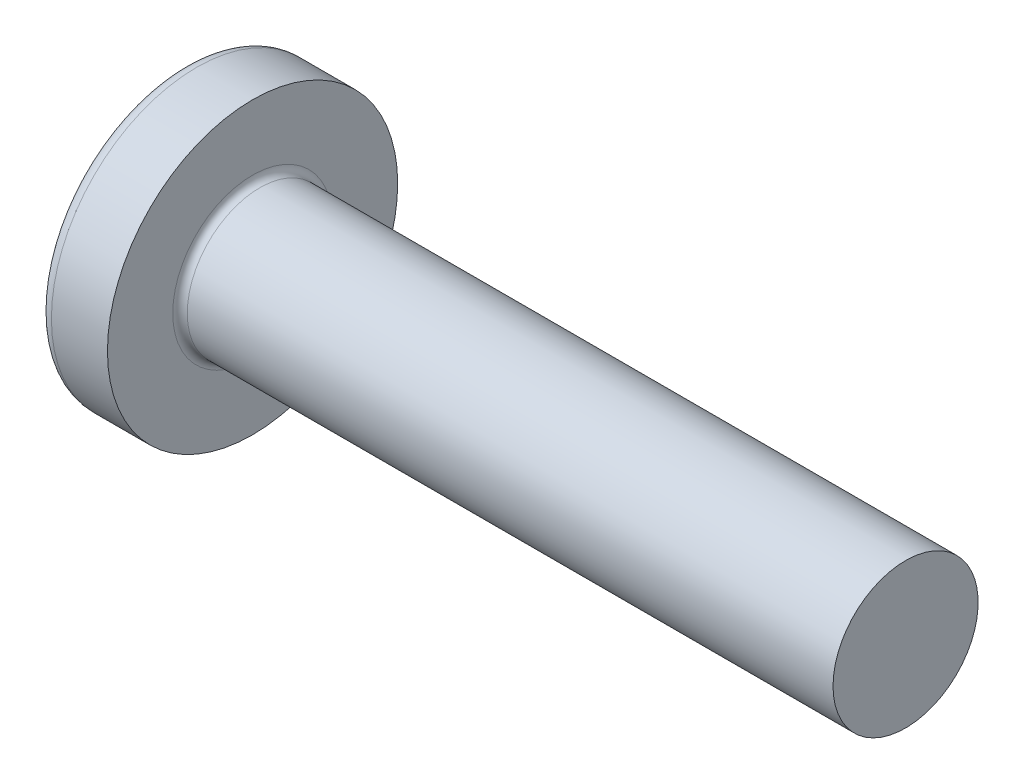
SolidWorks part; units mm, degrees
material "普通碳钢"
ref_plane "Plane1" through (0, 0, 0) normal (0, 0, 1) x (1, 0, 0)
ref_plane "Plane2" through (0, 0, 0) normal (0, 1, 0) x (1, 0, 0)
ref_plane "Plane3" through (0, 0, 0) normal (1, 0, 0) x (0, 0, -1)
sketch "BodySke" plane through (0, 0, 0) normal (0, 0, 1) x (1, 0, 0)
  line L0 (3.1, 2) -> (3.1, 4)
  line L1 (3.45, 6.35) -> (3.45, -3.175) construction
  line L2 (-25.4, 0) -> (127, 0) construction
  line L3 (21.1, 0) -> (0, 0)
  line L4 (3.1, 2) -> (21.1, 2)
  line L5 (21.1, 2) -> (21.1, 0)
  line L6 (1.5553, 4) -> (3.1, 4)
  line L8 (15.1, 6.35) -> (15.1, -3.175) construction
  arc A0 (1.2654, 3.8534) -> (0, 0) centre (6.5, 0) ccw
  arc A2 (1.2654, 3.8534) -> (1.5553, 4) centre (1.5553, 3.64) cw
  dimension "Head_fillet_rad" = 0.36
  dimension "Head_crown_rad" = 6.5
  dimension "Head_ht" = 3.1
  dimension "Diameter" = 4
  dimension "Length" = 18
  dimension "Head_dia" = 8
  dimension "Advance" = 0.7
  dimension "Thread_nom" = 6
revolve "Base-Revolve" add sketch "BodySke"
cosmetic thread "ThreadCosmetic" [suppressed]
fillet "Fillet1" radius 0.2 1 edges at (3.1, 0, 2)
sketch "Sketch3" plane through (0, 0, 0) normal (1, 0, 0) x (0, 0, -1)
  line L0 (0.515, -2.15) -> (-0.515, -2.15)
  line L1 (0.515, -2.15) -> (0.515, 2.15)
  line L2 (-0.515, 2.15) -> (0.515, 2.15)
  line L3 (-0.515, 2.15) -> (-0.515, -2.15)
  dimension "D1" = 2.15
  dimension "Cross_dia" = 4.3
  dimension "D2" = 0.515
  dimension "Cross_width" = 1.03
ref_plane "Plane4" through (2.34, 0, 0) normal (1, 0, 0) x (0, 0, -1)
sketch "Sketch4" plane through (2.34, 0, 0) normal (1, 0, 0) x (0, 0, -1)
  line L0 (0.515, -0.9833) -> (-0.515, -0.9833)
  line L1 (0.515, -0.9833) -> (0.515, 0.9833)
  line L2 (-0.515, 0.9833) -> (0.515, 0.9833)
  line L3 (-0.515, 0.9833) -> (-0.515, -0.9833)
  dimension "D1" = 1.03
  dimension "D2" = 1.9666
  dimension "D3" = 0.515
  dimension "D4" = 0.9833
loft "Recess" cut profiles "Sketch3", "Sketch4"
pattern_circular "RecPat" count 2 every 90 about axis through (0, 0, 0) along (1, 0, 0) of "Recess"
sketch "RecCorSke" plane through (0, 0, 0) normal (0, 0, 1) x (1, 0, 0)
  line L0 (-3.175, 0) -> (15.875, 0) construction
  line L1 (-25.4, 0) -> (127, 0) construction
  line L2 (0, 0) -> (0, 1.0146)
  line L3 (0, 1.0146) -> (2.34, 0.851)
  line L4 (2.34, 0.851) -> (2.6165, 0)
  line L5 (2.6165, 0) -> (0, 0)
  dimension "Diameter" = 1.702
  dimension "Depth" = 2.34
  dimension "Draft_angle" = 4
  dimension "Bottom_angle" = 18
revolve "RecessCore" cut sketch "RecCorSke" angle 360 about L0
sketch "ThdSchSke" plane through (0, 0, 0) normal (0, 0, 1) x (1, 0, 0)
  line L0 (9.1, -1.61) -> (8.8269, -2)
  line L1 (9.1, -1.61) -> (9.3731, -2)
  line L2 (9.3731, -2) -> (9.3731, -2.5)
  line L3 (-3.175, 0) -> (5.1513, 0) construction
  line L5 (9.3731, -2.5) -> (8.8269, -2.5)
  line L6 (8.8269, -2.5) -> (8.8269, -2)
  dimension "Thread_minor" = 3.22
  dimension "Diameter" = 4
  dimension "Start" = 9.1
  dimension "SideAngle" = 55
  dimension "VeeAngle" = 70
  dimension "Overcut" = 5
revolve "ThreadSchematic" [suppressed] cut sketch "ThdSchSke" angle 360 about L3
pattern_linear "ThdSchPat" [suppressed]
sketch "草图1" plane through (21.1, 0, 0) normal (1, 0, 0) x (0, 0, -1)
  circle A0 centre (0, 0) radius 2 construction
  circle A1 centre (0, 0) radius 2
equation "\"D1@Sketch3\" = \"Cross_dia@Sketch3\" / 2"
equation "\"D2@Sketch3\" = \"Cross_width@Sketch3\" / 2"
equation "\"Depth@RecCorSke\" = \"Cross_depth@Plane4\""
equation "\"D1@Sketch4\" = \"Cross_width@Sketch3\""
equation "\"D2@Sketch4\" = \"Cross_dia@Sketch3\" - 2.0 * \"Cross_depth@Plane4\" * tan(26.5  * 0.017453292)"
equation "\"D3@Sketch4\" = \"D1@Sketch4\" / 2"
equation "\"D4@Sketch4\" = \"D2@Sketch4\" / 2"
equation "\"Thread_length@ThreadCosmetic\" = ((sgn( (\"Length@BodySke\" - \"Advance@BodySke\" * 2.0 ) - \"Thread_nom@BodySke\" )-1)*( (\"Length@BodySke\" - \"Advance@BodySke\" * 2.0 ) - \"Thread_nom@BodySke\" ))/-2+ \"Thread_nom@BodySke\""
equation "\"Thread_minor@ThdSchSke\" = \"Thread_minor@ThreadCosmetic\""
equation "\"Diameter@ThdSchSke\" = \"Diameter@BodySke\""
equation "\"Overcut@ThdSchSke\" = \"Diameter@BodySke\" * 1.25"
equation "\"Start@ThdSchSke\" = \"Head_ht@BodySke\" + \"Length@BodySke\" - \"Thread_length@ThreadCosmetic\"  '---Non-countersunk---"
equation "\"Num_threads@ThdSchPat\" = int( \"Thread_length@ThreadCosmetic\" / \"Advance@BodySke\" + 0.999 )  + 1"
equation "\"Advance@ThdSchPat\" = \"Thread_length@ThreadCosmetic\" /  (\"Num_threads@ThdSchPat\" - 1) 'relax it"
